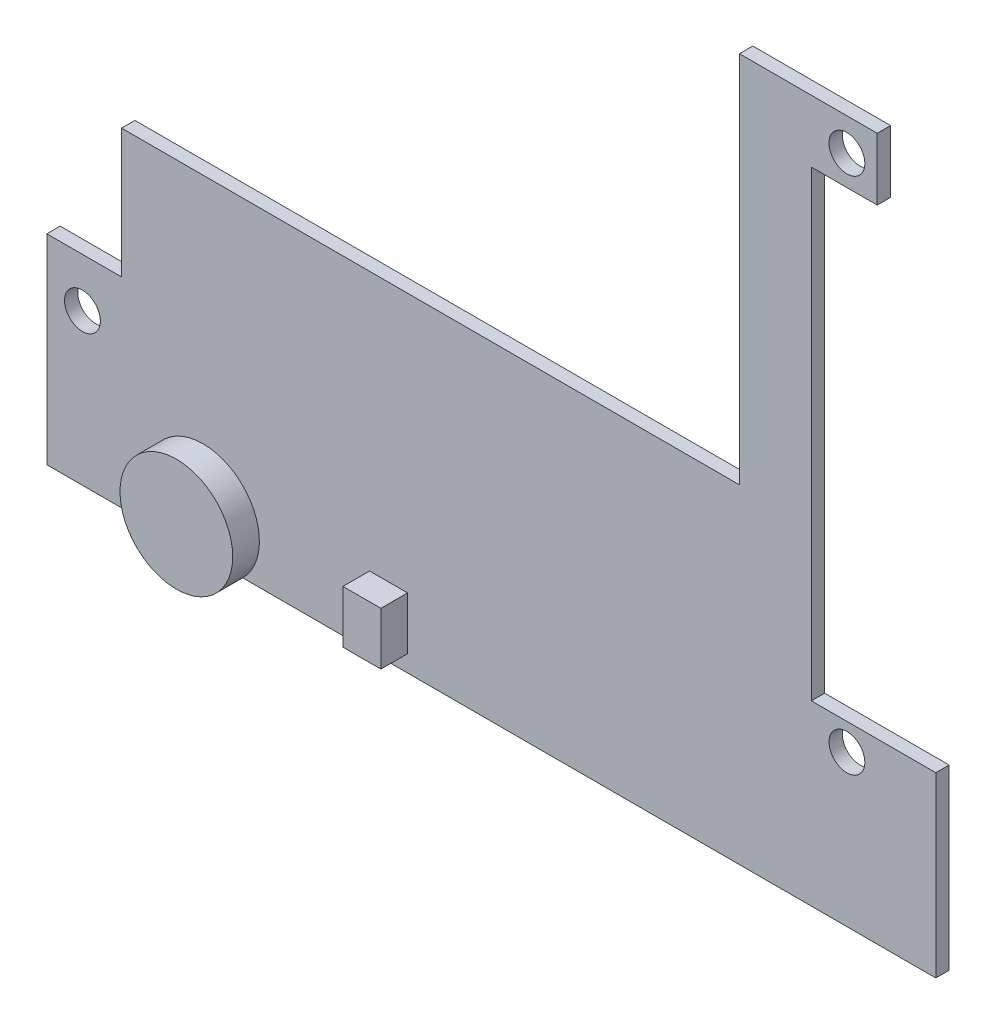
SolidWorks part; units mm, degrees
ref_plane "Front Plane" through (0, 0, 0) normal (0, 0, 1) x (1, 0, 0)
ref_plane "Top Plane" through (0, 0, 0) normal (0, 1, 0) x (1, 0, 0)
ref_plane "Right Plane" through (0, 0, 0) normal (1, 0, 0) x (0, 0, -1)
sketch "Sketch1" plane through (0, 0, 0) normal (0, 0, 1) x (1, 0, 0)
  line L0 (18.7247, 56.1741) -> (93.6235, 56.1741) construction
  line L1 (6.0967, 18.5255) -> (6.0967, 41.0255)
  line L2 (6.0967, 41.0255) -> (14.5048, 41.0255)
  line L3 (14.5048, 41.0255) -> (14.5048, 55.5255)
  line L4 (14.5048, 55.5255) -> (84.0048, 55.5255)
  line L5 (84.0048, 55.5255) -> (84.0048, 97.5255)
  line L6 (84.0048, 97.5255) -> (99.5048, 97.5255)
  line L7 (99.5048, 97.5255) -> (99.5048, 90.5255)
  line L8 (99.5048, 90.5255) -> (92.0967, 90.5255)
  line L9 (92.0967, 90.5255) -> (92.0967, 38.5255)
  line L10 (92.0967, 38.5255) -> (106.0967, 38.5255)
  line L11 (106.0967, 38.5255) -> (106.0967, 18.5255)
  line L12 (106.0967, 18.5255) -> (70.5325, 18.5255)
  line L13 (70.5325, 18.5255) -> (6.0967, 18.5255)
  circle A1 centre (96.0967, 35.5255) radius 2.0146
  circle A2 centre (96.0967, 93.875) radius 2.0146
  circle A3 centre (10.0967, 35.5255) radius 2.0146
  point P4 (96.0967, 93.875)
  point P31 (0, 0)
  point P32 (0, 0)
  dimension "D1" = 69.5
  dimension "D2" = 15.5
  dimension "D3" = 14
  dimension "D4" = 17
  dimension "D5" = 37
  dimension "22.5" = 22.5
  dimension "D6" = 86
  dimension "D7" = 100
  dimension "D8" = 20
  dimension "D9" = 10
  dimension "D10" = 52
  dimension "D11" = 79
extrude "Boss-Extrude1" add sketch "Sketch1" along normal blind 1.5
sketch "Sketch2" plane through (0, 0, 1.5) normal (0, 0, 1) x (1, 0, 0)
  line L1 (42.4008, 26.3291) -> (46.6714, 26.3291)
  line L2 (42.4008, 26.3291) -> (42.4008, 20.4054)
  line L3 (42.4008, 20.4054) -> (46.6714, 20.4054)
  line L4 (46.6714, 26.3291) -> (46.6714, 20.4054)
  circle A0 centre (23.6652, 23.0228) radius 6.3385
extrude "Boss-Extrude2" add sketch "Sketch2" along normal blind 3
